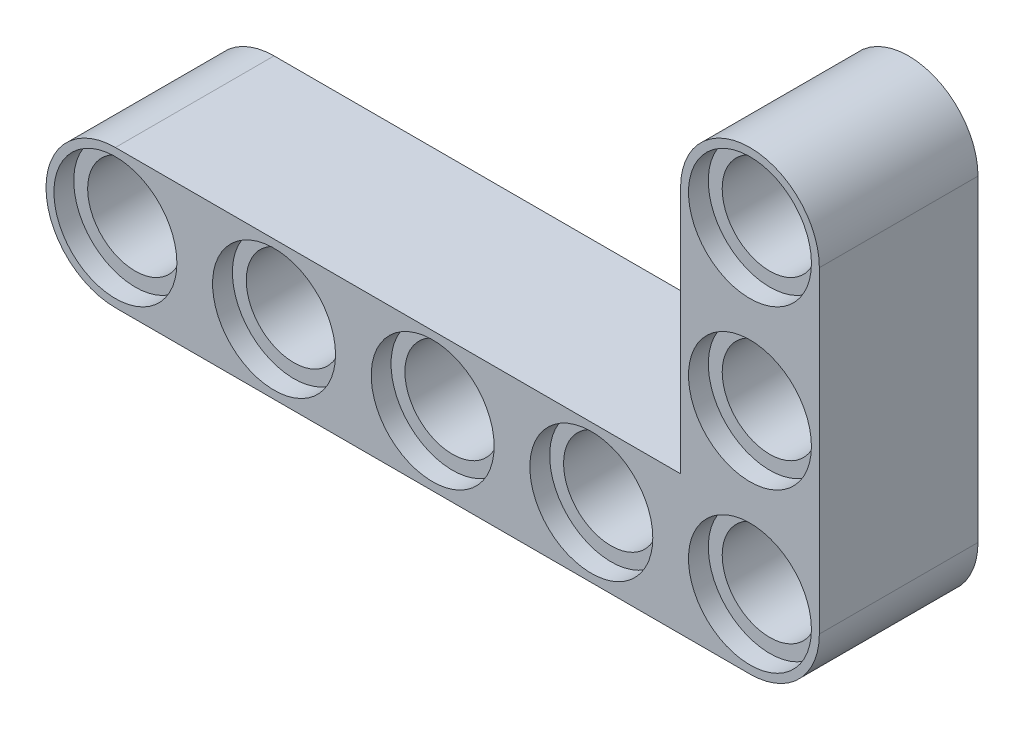
SolidWorks part; units mm, degrees
ref_plane "Front Plane" through (0, 0, 0) normal (0, 0, 1) x (1, 0, 0)
ref_plane "Top Plane" through (0, 0, 0) normal (0, 1, 0) x (1, 0, 0)
ref_plane "Right Plane" through (0, 0, 0) normal (1, 0, 0) x (0, 0, -1)
sketch "Sketch1" plane through (0, 0, 0) normal (0, 0, 1) x (1, 0, 0)
  line L14 (-16, -3.5) -> (16, -3.5)
  line L15 (19.5, 16) -> (19.5, 0)
  line L16 (12.5, 16) -> (12.5, 3.5)
  line L17 (-16, 3.5) -> (12.5, 3.5)
  circle A17 centre (0, 0) radius 2.4
  circle A18 centre (8, 0) radius 2.4
  circle A19 centre (16, 0) radius 2.4
  circle A20 centre (-8, 0) radius 2.4
  circle A21 centre (-16, 0) radius 2.4
  circle A22 centre (16, 8) radius 2.4
  circle A23 centre (16, 16) radius 2.4
  arc A27 (-16, 3.5) -> (-16, -3.5) centre (-16, 0) ccw
  arc A28 (12.5, 16) -> (19.5, 16) centre (16, 16) cw
  arc A29 (16, -3.5) -> (19.5, 0) centre (16, 0) ccw
  dimension "D1" = 4.8
  dimension "D2" = 8
  dimension "D3" = 4.8
  dimension "D5" = 4.8
  dimension "D7" = 4.8
  dimension "D9" = 4.8
  dimension "D13" = 4.8
  dimension "D15" = 4.8
  dimension "D6" = 8
  dimension "D4" = 8
  dimension "D8" = 8
  dimension "D11" = 3.5
  dimension "D12" = 8
  dimension "D14" = 8
extrude "Boss-Extrude1" add sketch "Sketch1" along normal mid plane 8
sketch "Sketch2" plane through (0, 0, 4) normal (0, 0, 1) x (1, 0, 0)
  circle A0 centre (-16, 0) radius 3.1
  circle A1 centre (-8, 0) radius 3.1
  circle A2 centre (0, 0) radius 3.1
  circle A3 centre (8, 0) radius 3.1
  circle A4 centre (16, 0) radius 3.1
  circle A5 centre (16, 8) radius 3.1
  circle A6 centre (16, 16) radius 3.1
  dimension "D1" = 6.2
  dimension "D2" = 6.2
  dimension "D3" = 6.2
  dimension "D4" = 6.2
  dimension "D5" = 6.2
  dimension "D6" = 6.2
  dimension "D7" = 6.2
extrude "Cut-Extrude1" cut sketch "Sketch2" against normal blind 1
mirror "Mirror1" about plane through (0, 0, 0) normal (0, 0, 1) of "Cut-Extrude1"
